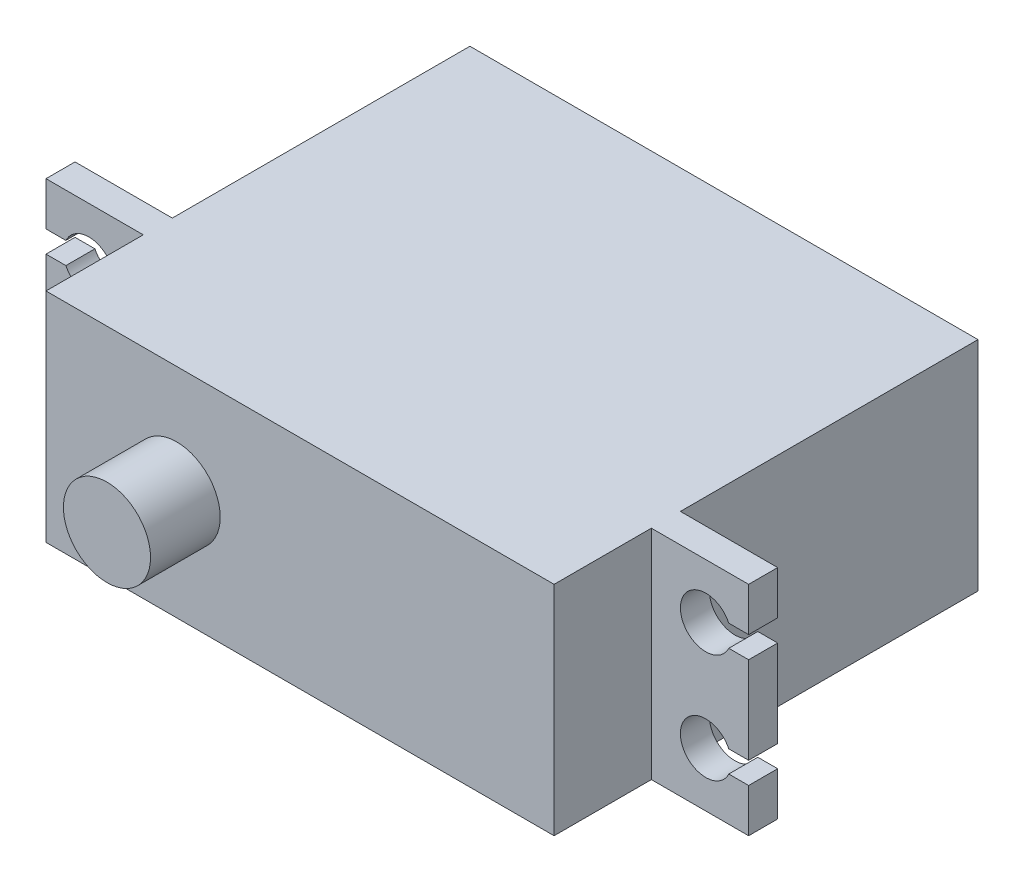
SolidWorks part; units mm, degrees
ref_plane "Płaszczyzna przednia" through (0, 0, 0) normal (0, 0, 1) x (1, 0, 0)
ref_plane "Płaszczyzna górna" through (0, 0, 0) normal (0, 1, 0) x (1, 0, 0)
ref_plane "Płaszczyzna prawa" through (0, 0, 0) normal (1, 0, 0) x (0, 0, -1)
sketch "Szkic1" plane through (0, 0, 0) normal (0, 0, 1) x (1, 0, 0)
  line L1 (-17.5, 7.5) -> (17.5, 7.5)
  line L2 (-17.5, 7.5) -> (-17.5, -7.5)
  line L3 (-17.5, -7.5) -> (17.5, -7.5)
  line L4 (17.5, 7.5) -> (17.5, -7.5)
  line L5 (-17.5, 7.5) -> (17.5, -7.5) construction
  line L6 (-17.5, -7.5) -> (17.5, 7.5) construction
  point P0 (0, 0)
  dimension "D1" = 15
  dimension "D2" = 35
extrude "Dodanie-wyciągnięcie1" add sketch "Szkic1" along normal blind 20.5
sketch "Szkic2" plane through (0, 0, 20.5) normal (0, 0, 1) x (1, 0, 0)
  line L0 (17.5, -7.5) -> (29.0923, -7.5) construction
  line L1 (-21.25, 13.1634) -> (-21.25, -10.9725) construction
  line L2 (-24.2, 7.5) -> (24.2, 7.5)
  line L3 (-24.2, 7.5) -> (-24.2, 4.5)
  line L4 (-24.2, -7.5) -> (24.2, -7.5)
  line L5 (24.2, 7.5) -> (24.2, 4.5)
  line L6 (-24.2, 7.5) -> (24.2, -7.5) construction
  line L7 (-24.2, -7.5) -> (24.2, 7.5) construction
  line L8 (21.25, 10.1105) -> (21.25, -11.8704) construction
  line L9 (-24.2, 3) -> (-24.2, -3)
  line L10 (-21.25, -3.75) -> (21.25, -3.75) construction
  line L11 (-24.2, -4.5) -> (-24.2, -7.5)
  line L12 (-24.2, 4.5) -> (-22.8311, 4.5)
  line L14 (-24.2, 3) -> (-22.8311, 3)
  line L16 (-24.2, -3) -> (-22.8311, -3)
  line L18 (-21.25, 3.75) -> (21.25, 3.75) construction
  line L19 (-24.2, -4.5) -> (-22.8311, -4.5)
  line L21 (24.2, 3) -> (24.2, -3)
  line L22 (24.2, 4.5) -> (22.8311, 4.5)
  line L24 (24.2, 3) -> (22.8311, 3)
  line L26 (24.2, -4.5) -> (24.2, -7.5)
  line L28 (24.2, -3) -> (22.8311, -3)
  line L30 (24.2, -4.5) -> (22.8311, -4.5)
  arc A0 (-22.8311, 3) -> (-22.8311, 4.5) centre (-21.25, 3.75) ccw
  arc A1 (-22.8311, -4.5) -> (-22.8311, -3) centre (-21.25, -3.75) ccw
  arc A2 (22.8311, 4.5) -> (22.8311, 3) centre (21.25, 3.75) ccw
  arc A3 (22.8311, -3) -> (22.8311, -4.5) centre (21.25, -3.75) ccw
  point P2 (0, 0)
  point P13 (-24.2, -3.75)
  point P15 (24.2, 3.75)
  point P25 (-24.2, 3.75)
  point P36 (24.2, -3.75)
  dimension "D6" = 3.5
  dimension "D1" = 48.4
  dimension "D2" = 42.5
  dimension "D3" = 2.95
  dimension "D4" = 1.5
extrude "Dodanie-wyciągnięcie2" add sketch "Szkic2" along normal blind 2
sketch "Szkic3" plane through (0, 0, 22.5) normal (0, 0, 1) x (1, 0, 0)
  line L0 (-24.2, -7.5) -> (24.2, -7.5) construction
  line L1 (-17.5, 7.5) -> (17.5, 7.5)
  line L2 (-17.5, 7.5) -> (-17.5, -7.5)
  line L3 (-17.5, -7.5) -> (17.5, -7.5)
  line L4 (17.5, 7.5) -> (17.5, -7.5)
  line L5 (-17.5, 7.5) -> (17.5, -7.5) construction
  line L6 (-17.5, -7.5) -> (17.5, 7.5) construction
  point P0 (0, 0)
  dimension "D1" = 35
extrude "Dodanie-wyciągnięcie3" add sketch "Szkic3" along normal blind 6.7
sketch "Szkic4" plane through (0, 0, 29.2) normal (0, 0, 1) x (1, 0, 0)
  line L0 (-17.5, 7.5) -> (-17.5, -7.5) construction
  line L1 (-17.5, 0) -> (17.5, 0) construction
  line L2 (-17.5, 7.5) -> (-17.5, -7.5) construction
  line L3 (17.5, -7.5) -> (17.5, 7.5) construction
  circle A0 centre (-8.5, 0) radius 3
  dimension "D1" = 9
extrude "Dodanie-wyciągnięcie4" add sketch "Szkic4" along normal blind 4.8
